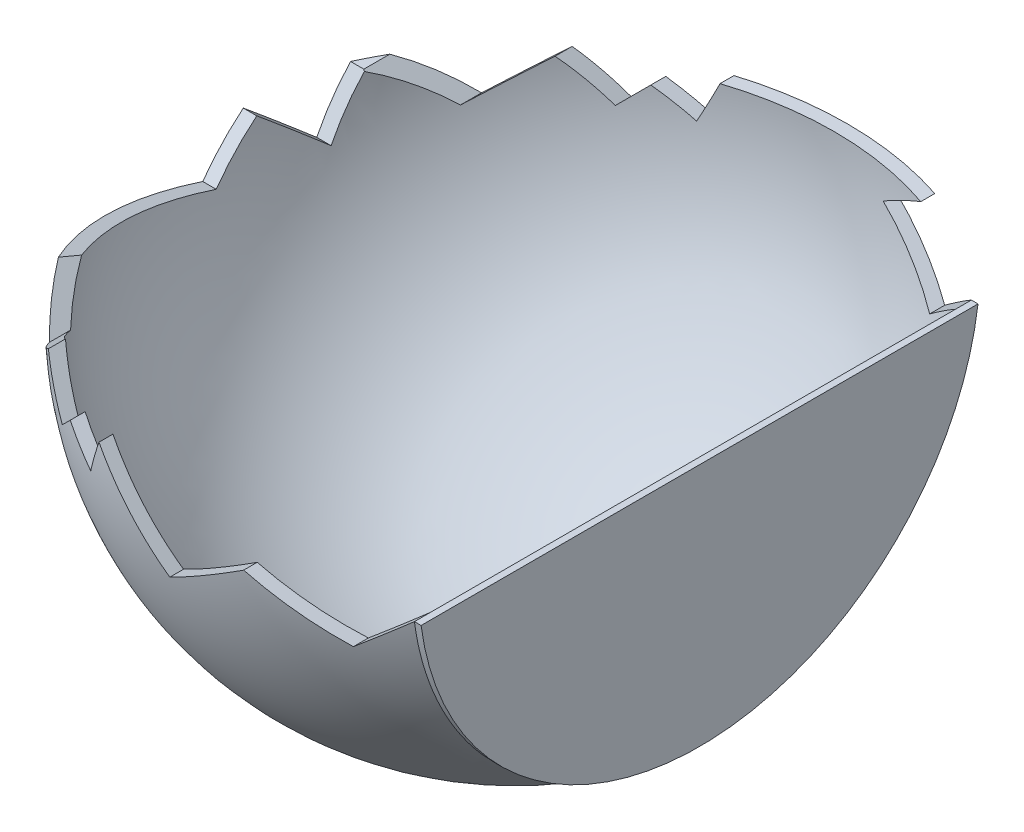
SolidWorks part; units mm, degrees
ref_plane "Front Plane" through (0, 0, 0) normal (0, 0, 1) x (1, 0, 0)
ref_plane "Top Plane" through (0, 0, 0) normal (0, 1, 0) x (1, 0, 0)
ref_plane "Right Plane" through (0, 0, 0) normal (1, 0, 0) x (0, 0, -1)
sketch "Sketch3" plane through (0, 0, 0) normal (0, 1, 0) x (1, 0, 0)
  line L0 (0, 50) -> (0, -50)
  arc A0 (0, 50) -> (0, -50) centre (0, 0) ccw
  dimension "D1" = 100
revolve "Revolve7" add sketch "Sketch3" angle 180 about L0
shell "Shell1" thickness 2
ref_plane "Plane1" through (0, 0, 50) normal (0, 0, 1) x (1, 0, 0)
sketch "Sketch7" plane through (0, 0, 50) normal (0, 0, 1) x (1, 0, 0)
  line L0 (-14.8264, 0) -> (-3.3708, -11.4556)
  line L1 (48, 0) -> (-48, 0) construction
  line L2 (-3.3708, -11.4556) -> (15.6455, 0)
  line L3 (50, 0) -> (-50, 0) construction
  line L4 (15.6455, 0) -> (-14.8264, 0)
extrude "Cut-Extrude1" cut sketch "Sketch7" against normal blind 10
sketch "Sketch9" plane through (0, 0, 50) normal (0, 0, 1) x (1, 0, 0)
  line L0 (8.292, -4.4298) -> (20.1508, -10.788)
  line L1 (15.6455, 0) -> (-3.3708, -11.4556) construction
  line L2 (20.1508, -10.788) -> (33.6666, 0)
  line L3 (50, 0) -> (-50, 0) construction
  line L4 (33.6666, 0) -> (15.6455, 0)
  line L5 (8.292, -4.4298) -> (15.6455, 0)
extrude "Cut-Extrude2" cut sketch "Sketch9" against normal through all both and the other way through all
sketch "Sketch10" plane through (0, 0, 50) normal (0, 0, 1) x (1, 0, 0)
  line L0 (-43.4962, 0) -> (-37.5289, -5.9674)
  line L1 (15.6455, 0) -> (-48, 0) construction
  line L2 (-37.5289, -5.9674) -> (-30.7996, 0)
  line L3 (-30.7996, 0) -> (-25.3237, -5.4759)
  line L4 (-25.3237, -5.4759) -> (-22.1167, -2.2689)
  line L5 (-22.1167, -2.2689) -> (-17.1772, -5.4759)
  line L6 (-17.1772, -5.4759) -> (-14.8264, 0)
  line L7 (-14.8264, 0) -> (-43.4962, 0)
  line L8 (-43.4962, 0) -> (-43.5031, -0.0626)
extrude "Cut-Extrude3" cut sketch "Sketch10" against normal through all both and the other way through all contours L2 L7 L0 | L6 L7 L3 L4 L5
ref_plane "Plane2" through (50, 0, 0) normal (1, 0, 0) x (0, 0, -1)
sketch "Sketch12" plane through (50, 0, 0) normal (1, 0, 0) x (0, 0, -1)
  line L0 (-28.8047, 0) -> (2.2811, -8.2772)
  line L1 (36.967, 0) -> (-36.967, 0) construction
  line L2 (2.2811, -8.2772) -> (8.3843, -1.767)
  line L3 (8.3843, -1.767) -> (16.6033, -8.2772)
  line L4 (16.6033, -8.2772) -> (20.7535, 0)
  line L5 (20.7535, 0) -> (-28.8047, 0)
extrude "Cut-Extrude10" cut sketch "Sketch12" against normal blind 150 contours L4 L5 L0 L2 L3
ref_plane "Plane3" through (26.7489, 0, 0) normal (1, 0, 0) x (0, 0, -1)
split "Split1" trim tools "Plane3" bodies to split 106 resulting bodies 107
sketch "Sketch15" plane through (26.7489, 0, 0) normal (1, 0, 0) x (0, 0, -1)
  line L0 (-41.8809, -5.5215) -> (41.8809, -5.5215)
  line L1 (41.8809, -5.5215) -> (39.4716, -5.5215) construction
  arc A0 (-41.8809, -5.5215) -> (41.8809, -5.5215) centre (0, 0) ccw
extrude "Boss-Extrude1" add sketch "Sketch15" along normal blind 1
